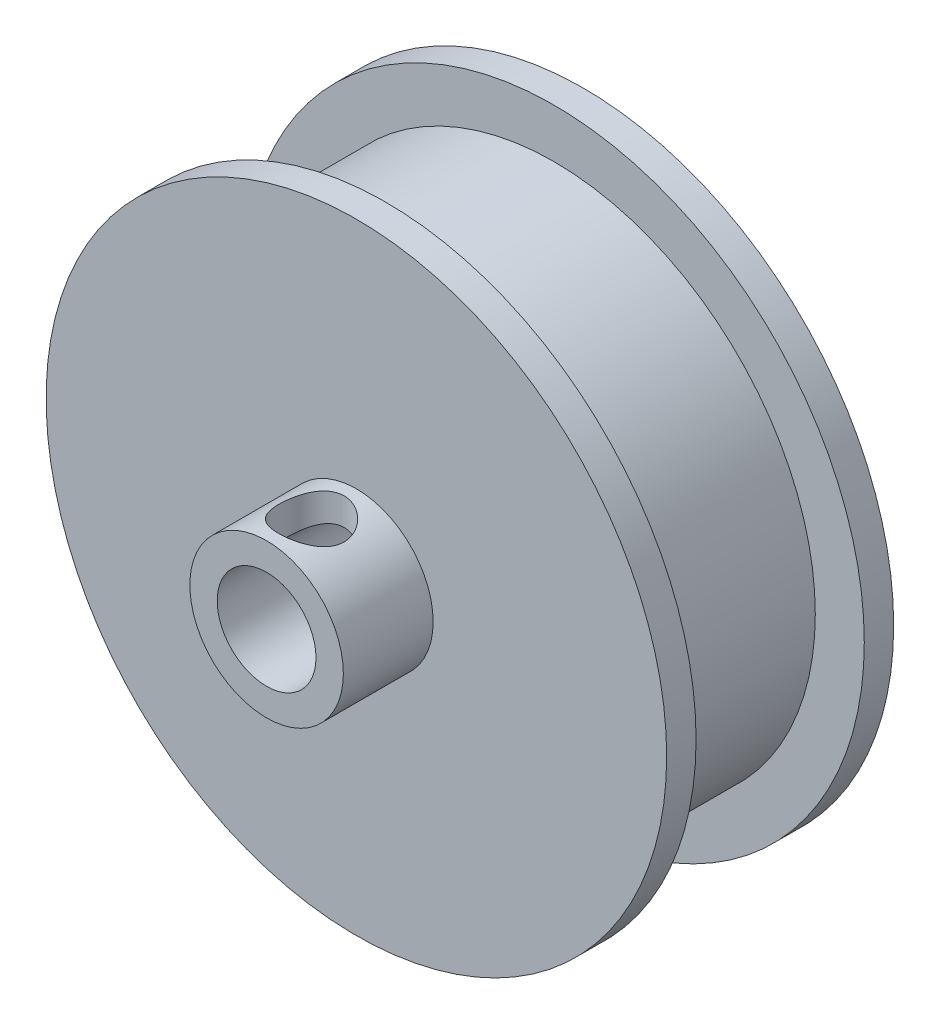
SolidWorks part; units mm, degrees
ref_plane "Plan de face" through (0, 0, 0) normal (0, 0, 1) x (1, 0, 0)
ref_plane "Plan de dessus" through (0, 0, 0) normal (0, 1, 0) x (1, 0, 0)
ref_plane "Plan de droite" through (0, 0, 0) normal (1, 0, 0) x (0, 0, -1)
sketch "Esquisse1" plane through (0, 0, 0) normal (0, 0, 1) x (1, 0, 0)
  circle A0 centre (0, 0) radius 3.025
  circle A1 centre (0, 0) radius 19
  dimension "D1" = 6.05
  dimension "D2" = 38
extrude "Boss.-Extru.1" add sketch "Esquisse1" along normal mid plane 13.9
sketch "Esquisse2" plane through (0, 0, 0) normal (0, 0, 1) x (1, 0, 0)
  circle A0 centre (0, 0) radius 16
  circle A1 centre (0, 0) radius 50
  dimension "D1" = 32
  dimension "D2" = 100
extrude "Enlèv. mat.-Extru.1" cut sketch "Esquisse2" against normal mid plane 10.3
sketch "Esquisse4" plane through (0, 0, 6.95) normal (0, 0, 1) x (1, 0, 0)
  circle A0 centre (0, 0) radius 4.7
  circle A1 centre (0, 0) radius 3.025
  dimension "D1" = 9.4
extrude "Boss.-Extru.2" add sketch "Esquisse4" along normal blind 5.5
sketch "Esquisse5" plane through (0, 0, 0) normal (0, 1, 0) x (1, 0, 0)
  line L0 (-4.7, -12.45) -> (4.7, -12.45) construction
  circle A0 centre (0, -9.7) radius 2
  dimension "D1" = 4
  dimension "D2" = 2.75
extrude "Enlèv. mat.-Extru.3" cut sketch "Esquisse5" along normal through all
